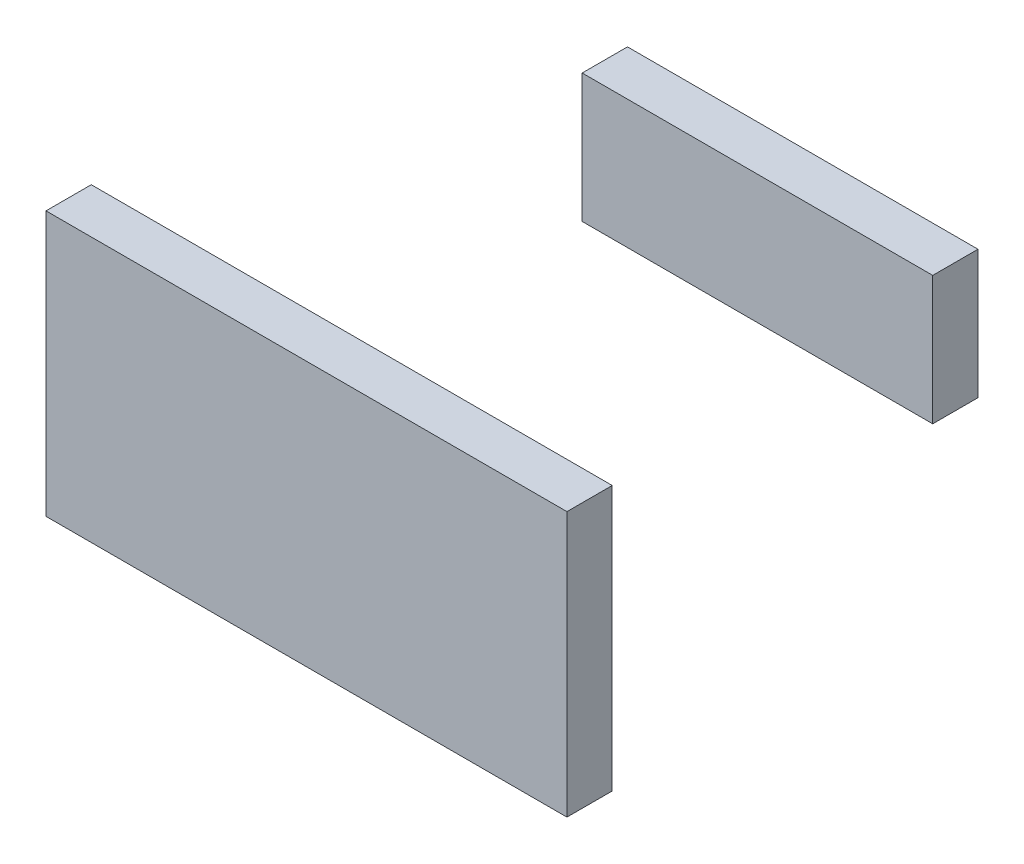
SolidWorks part; units mm, degrees
ref_plane "Plan de face" through (0, 0, 0) normal (0, 0, 1) x (1, 0, 0)
ref_plane "Plan de dessus" through (0, 0, 0) normal (0, 1, 0) x (1, 0, 0)
ref_plane "Plan de droite" through (0, 0, 0) normal (1, 0, 0) x (0, 0, -1)
ref_plane "Plan1" through (0, 0, -50) normal (0, 0, 1) x (1, 0, 0)
ref_plane "Plan2" through (0, 0, 50) normal (0, 0, 1) x (1, 0, 0)
sketch "Esquisse2" plane through (0, 0, 50) normal (0, 0, 1) x (1, 0, 0)
  line L1 (-48.9476, 30.2269) -> (66.1157, 30.2269)
  line L2 (-48.9476, 30.2269) -> (-48.9476, -28.2179)
  line L3 (-48.9476, -28.2179) -> (66.1157, -28.2179)
  line L4 (66.1157, 30.2269) -> (66.1157, -28.2179)
extrude "Boss.-Extru.1" add sketch "Esquisse2" along normal blind 10
sketch "Esquisse3" plane through (0, 0, -50) normal (0, 0, 1) x (1, 0, 0)
  line L1 (-30.5127, 15.8128) -> (46.9097, 15.8128)
  line L2 (-30.5127, 15.8128) -> (-30.5127, -12.5885)
  line L3 (-30.5127, -12.5885) -> (46.9097, -12.5885)
  line L4 (46.9097, 15.8128) -> (46.9097, -12.5885)
extrude "Boss.-Extru.2" add sketch "Esquisse3" along normal blind 10 separate body
